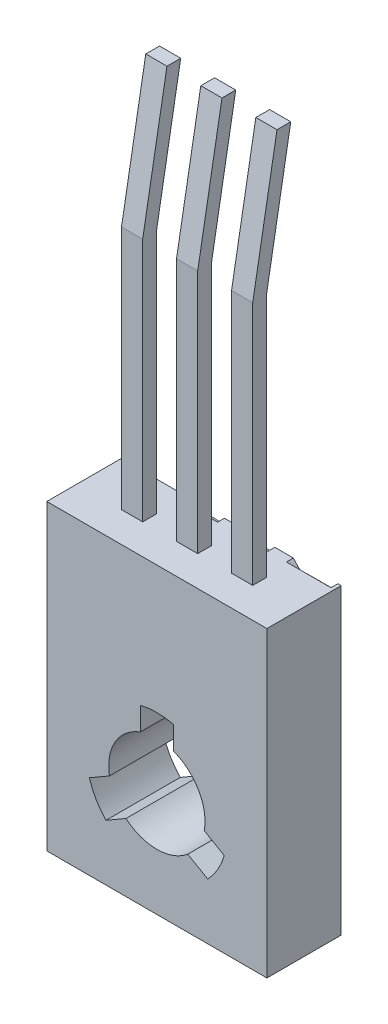
SolidWorks part; units mm, degrees
ref_plane "Front Plane" through (0, 0, 0) normal (0, 0, 1) x (1, 0, 0)
ref_plane "Top Plane" through (0, 0, 0) normal (0, 1, 0) x (1, 0, 0)
ref_plane "Right Plane" through (0, 0, 0) normal (1, 0, 0) x (0, 0, -1)
sketch "Sketch1" plane through (0, 0, 0) normal (0, 0, 1) x (1, 0, 0)
  line L1 (-4, 5.5) -> (4, 5.5)
  line L2 (-4, 5.5) -> (-4, -5.5)
  line L3 (-4, -5.5) -> (4, -5.5)
  line L4 (4, 5.5) -> (4, -5.5)
  line L5 (-4, 5.5) -> (4, -5.5) construction
  line L6 (-4, -5.5) -> (4, 5.5) construction
  circle A0 centre (0, -1.7) radius 2.555
  point P0 (0, 0)
  dimension "D3" = 5.11
  dimension "D1" = 11
  dimension "D2" = 8
  dimension "D4" = 3.8
extrude "Boss-Extrude1" add sketch "Sketch1" along normal mid plane 2.7
sketch "Sketch2" plane through (0, 5.5, 0) normal (0, 1, 0) x (1, 0, 0)
  line L0 (0, 0.8819) -> (0, -0.7814) construction
  line L1 (-0.385, 0.25) -> (0.385, 0.25)
  line L2 (-0.385, 0.25) -> (-0.385, -0.25)
  line L3 (-0.385, -0.25) -> (0.385, -0.25)
  line L4 (0.385, 0.25) -> (0.385, -0.25)
  line L5 (-0.385, 0.25) -> (0.385, -0.25) construction
  line L6 (-0.385, -0.25) -> (0.385, 0.25) construction
  line L7 (-2.385, 0.25) -> (-1.615, 0.25)
  line L8 (-2.385, 0.25) -> (-2.385, -0.25)
  line L9 (-2.385, -0.25) -> (-1.615, -0.25)
  line L10 (-1.615, 0.25) -> (-1.615, -0.25)
  line L11 (-2.385, 0.25) -> (-1.615, -0.25) construction
  line L12 (-2.385, -0.25) -> (-1.615, 0.25) construction
  line L13 (2.385, -0.25) -> (1.615, -0.25)
  line L14 (1.615, 0.25) -> (1.615, -0.25)
  line L15 (2.385, 0.25) -> (1.615, 0.25)
  line L16 (2.385, 0.25) -> (2.385, -0.25)
  point P0 (0, 0)
  point P7 (-2, 0)
  dimension "D1" = 0.5
  dimension "D2" = 0.77
  dimension "D3" = 0.77
  dimension "D4" = 0.5
  dimension "D5" = 2
extrude "Boss-Extrude2" add sketch "Sketch2" along normal blind 8.9
sketch "Sketch4" plane through (0, 0, 1.35) normal (0, 0, 1) x (1, 0, 0)
  line L0 (0, 0.8936) -> (0, -1.7) construction
  line L3 (-0.6, 0.8232) -> (-0.6, -0.0561)
  line L4 (0.6, 0.8232) -> (0.6, -0.0561)
  line L5 (2.4852, -2.442) -> (1.7237, -2.0023)
  line L6 (1.8852, -3.4812) -> (1.1237, -3.0416)
  line L7 (-1.8852, -3.4812) -> (-1.1237, -3.0416)
  line L8 (-2.4852, -2.442) -> (-1.7237, -2.0023)
  arc A0 (-1.1237, -3.0416) -> (1.1237, -3.0416) centre (0, -1.7) ccw
  arc A1 (-1.8852, -3.4812) -> (1.8852, -3.4812) centre (0, -1.7) ccw
  arc A2 (-0.6, -0.0561) -> (-1.7237, -2.0023) centre (0, -1.7) ccw
  arc A3 (-0.6, 0.8232) -> (-2.4852, -2.442) centre (0, -1.7) ccw
  arc A4 (1.7237, -2.0023) -> (0.6, -0.0561) centre (0, -1.7) ccw
  arc A5 (2.4852, -2.442) -> (0.6, 0.8232) centre (0, -1.7) ccw
  point P22 (0, -1.7)
  dimension "D1" = 3.5
  dimension "D2" = 0.6
  dimension "D3" = 3
extrude "Boss-Extrude3" add sketch "Sketch4" against normal up to surface (2.7 mm away) up to face at (0, 0, -1.35)
sketch "Sketch5" plane through (0, 0, -1.35) normal (0, 0, -1) x (-1, 0, 0)
  text T0 "D882" font "Century Gothic" height in points 9
extrude "Cut-Extrude1" cut sketch "Sketch5" against normal blind 0.25
sketch "Sketch7" plane through (0, 0, 0) normal (1, 0, 0) x (0, 0, -1)
  line L0 (0, 14.4) -> (0.8821, 19.4028)
  line L1 (-0.25, 14.4) -> (0.25, 14.4) construction
  line L2 (0.25, 14.4) -> (0.25, 5.5) construction
  dimension "D1" = 10
  dimension "D2" = 5.08
sketch "Sketch8" plane through (0, 14.4, 0) normal (0, 1, 0) x (1, 0, 0)
  line L0 (2.385, -0.25) -> (2.385, 0.25) construction
  line L1 (2.385, 0.25) -> (1.615, 0.25) construction
  line L2 (1.615, 0.25) -> (1.615, -0.25) construction
  line L3 (1.615, -0.25) -> (2.385, -0.25) construction
  line L4 (0.385, -0.25) -> (0.385, 0.25) construction
  line L5 (0.385, 0.25) -> (-0.385, 0.25) construction
  line L6 (-0.385, 0.25) -> (-0.385, -0.25) construction
  line L7 (-0.385, -0.25) -> (0.385, -0.25) construction
  line L8 (-1.615, -0.25) -> (-1.615, 0.25) construction
  line L9 (-1.615, 0.25) -> (-2.385, 0.25) construction
  line L10 (-2.385, 0.25) -> (-2.385, -0.25) construction
  line L11 (-2.385, -0.25) -> (-1.615, -0.25) construction
  line L12 (2.385, -0.25) -> (2.385, 0.25)
  line L13 (2.385, 0.25) -> (1.615, 0.25)
  line L14 (1.615, 0.25) -> (1.615, -0.25)
  line L15 (1.615, -0.25) -> (2.385, -0.25)
  line L16 (0.385, -0.25) -> (0.385, 0.25)
  line L17 (0.385, 0.25) -> (-0.385, 0.25)
  line L18 (-0.385, 0.25) -> (-0.385, -0.25)
  line L19 (-0.385, -0.25) -> (0.385, -0.25)
  line L20 (-1.615, -0.25) -> (-1.615, 0.25)
  line L21 (-1.615, 0.25) -> (-2.385, 0.25)
  line L22 (-2.385, 0.25) -> (-2.385, -0.25)
  line L23 (-2.385, -0.25) -> (-1.615, -0.25)
sweep "Sweep1" add profiles "Sketch8" path "Sketch7"
